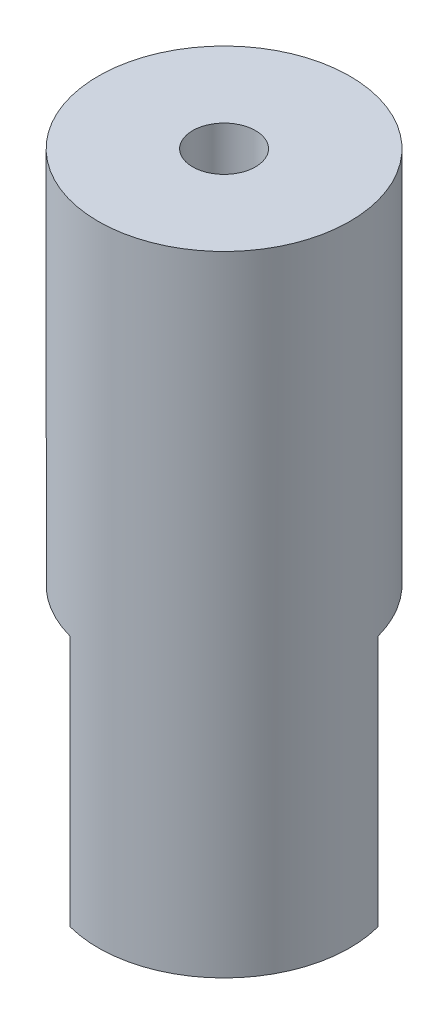
SolidWorks part; units mm, degrees
ref_plane "Front Plane" through (0, 0, 0) normal (0, 0, 1) x (1, 0, 0)
ref_plane "Top Plane" through (0, 0, 0) normal (0, 1, 0) x (1, 0, 0)
ref_plane "Right Plane" through (0, 0, 0) normal (1, 0, 0) x (0, 0, -1)
sketch "Sketch1" plane through (0, 0, 0) normal (0, 1, 0) x (1, 0, 0)
  circle A0 centre (0, 0) radius 10
  dimension "D1" = 20
extrude "Boss-Extrude1" add sketch "Sketch1" along normal blind 30
hole_wizard "Ø5.0mm Dowel Hole1" positions "Sketch4" profile "Sketch3" hole size "Ø5.0" standard "ANSI Metric" end condition through all
sketch "Sketch4" plane through (0, 30, 0) normal (0, 1, 0) x (1, 0, 0)
  point P0 (0, 0)
sketch "Sketch3" plane through (0, 30, 0) normal (1, 0, 0) x (0, 0, 1)
  line L0 (0, 0) -> (0, 30)
  line L1 (0, 30) -> (2.5, 30)
  line L2 (2.5, 30) -> (2.5, 0)
  line L5 (2.5, 0) -> (0, 0)
  line L11 (0, -6.35) -> (0, 107.95) construction
  dimension "Thru Hole Dia." = 5
  dimension "Thru Hole Depth" = 30
sketch "Croquis1" plane through (0, 0, 0) normal (0, -1, 0) x (1, 0, 0)
  line L0 (9.6593, -2.5882) -> (-2.5882, 9.6593)
  arc A2 (9.6593, -2.5882) -> (-2.5882, 9.6593) centre (0, 0) ccw
  point P6 (11.2762, -4.1046)
  point P8 (-4.1046, 11.2762)
  dimension "D1" = 5
extrude "Saliente-Extruir1" add sketch "Croquis1" along normal blind 20
